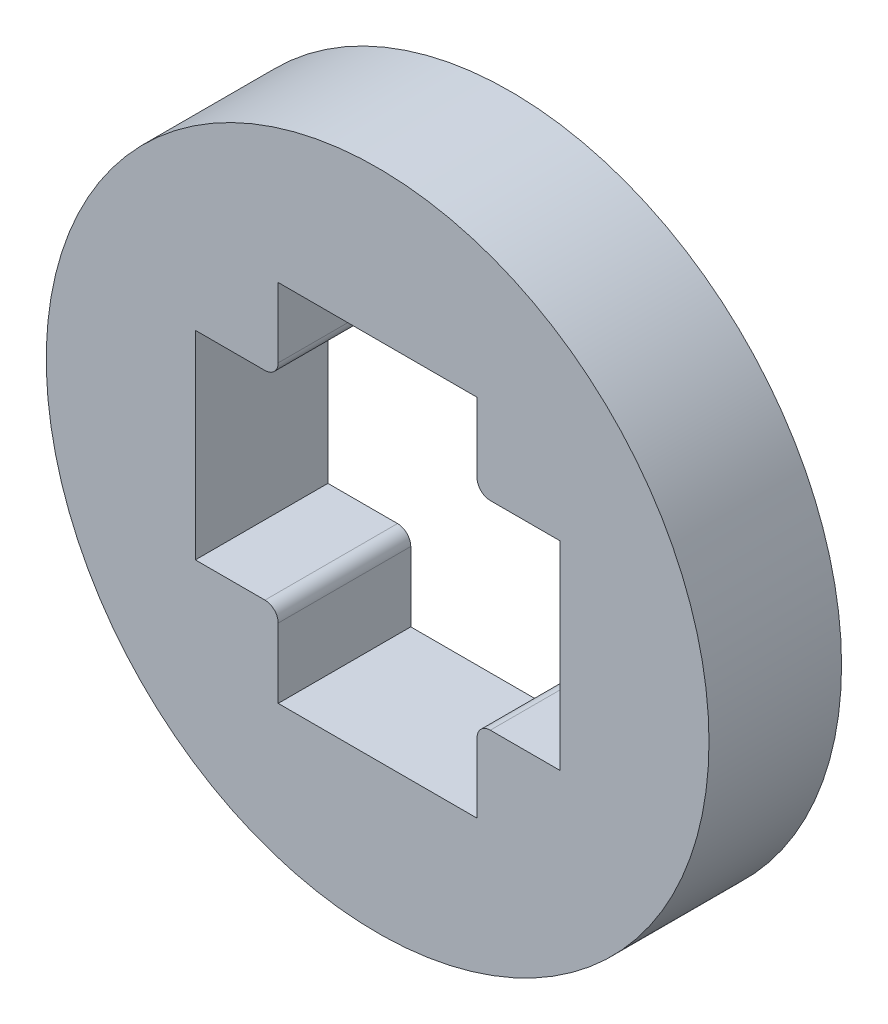
SolidWorks part; units mm, degrees
ref_plane "Front Plane" through (0, 0, 0) normal (0, 0, 1) x (1, 0, 0)
ref_plane "Top Plane" through (0, 0, 0) normal (0, 1, 0) x (1, 0, 0)
ref_plane "Right Plane" through (0, 0, 0) normal (1, 0, 0) x (0, 0, -1)
sketch "Sketch1" plane through (0, 0, 0) normal (0, 0, 1) x (1, 0, 0)
  line L1 (-2.75, 1.5) -> (2.75, 1.5)
  line L2 (-2.75, 1.5) -> (-2.75, -1.5)
  line L3 (-2.75, -1.5) -> (2.75, -1.5)
  line L4 (2.75, 1.5) -> (2.75, -1.5)
  line L5 (-2.75, 1.5) -> (2.75, -1.5) construction
  line L6 (-2.75, -1.5) -> (2.75, 1.5) construction
  line L7 (1.5, 2.75) -> (-1.5, 2.75)
  line L8 (1.5, 2.75) -> (1.5, -2.75)
  line L9 (1.5, -2.75) -> (-1.5, -2.75)
  line L10 (-1.5, 2.75) -> (-1.5, -2.75)
  line L11 (1.5, 2.75) -> (-1.5, -2.75) construction
  line L12 (1.5, -2.75) -> (-1.5, 2.75) construction
  circle A0 centre (0, 0) radius 5
  dimension "D1" = 10
  dimension "D2" = 3
  dimension "D3" = 5.5
  dimension "D4" = 5.5
  dimension "D5" = 3
extrude "Boss-Extrude2" add sketch "Sketch1" along normal blind 2 contours A0 L10 L7 L8 L1 L4 L3 L9 L2
fillet "Fillet2" radius 0.2 4 edges at (-1.5, 1.5, 1) (-1.5, -1.5, 1) (1.5, -1.5, 1) (1.5, 1.5, 1)
